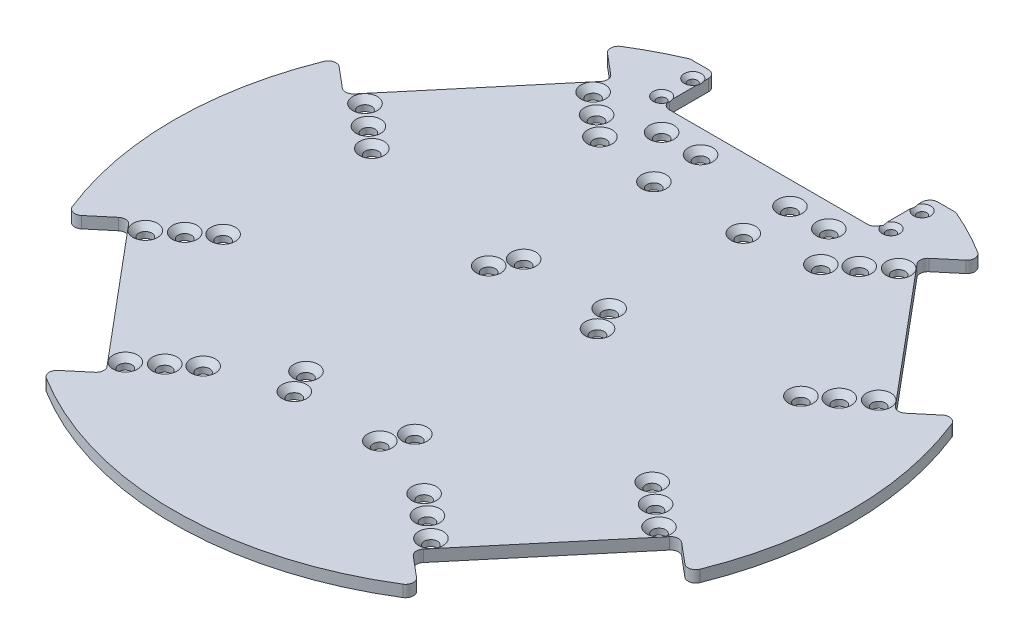
SolidWorks part; units mm, degrees
material "Liga 1060"
ref_plane "Plano frontal" through (0, 0, 0) normal (0, 0, 1) x (1, 0, 0)
ref_plane "Plano superior" through (0, 0, 0) normal (0, 1, 0) x (1, 0, 0)
ref_plane "Plano direito" through (0, 0, 0) normal (1, 0, 0) x (0, 0, -1)
sketch "Esboço1" plane through (0, 0, 0) normal (0, 1, 0) x (1, 0, 0)
  line L0 (0, 0) -> (0, 57.579) construction
  line L1 (0, 0) -> (28.8198, 0) construction
  circle A0 centre (0, 0) radius 87
  dimension "D1" = 174
extrude "Ressalto-extrusão2" add sketch "Esboço1" along normal blind 3
sketch "Esboço2" plane through (0, 3, 0) normal (0, 1, 0) x (1, 0, 0)
  line L0 (-87, 0) -> (87, 0) construction
  line L1 (0, 0) -> (66.6459, 55.9225) construction
  line L2 (0, 0) -> (66.6459, -55.9225) construction
  line L3 (48.2004, 72.4274) -> (79.697, 34.8912) construction
  line L4 (39.3908, 65.0353) -> (70.8874, 27.4991)
  line L9 (70.8874, 27.4991) -> (82.3942, 37.1544)
  line L10 (66.6459, 55.9225) -> (82.3942, 37.1544)
  line L11 (66.6459, 55.9225) -> (50.8976, 74.6906)
  line L12 (39.3908, 65.0353) -> (50.8976, 74.6906)
  line L13 (50.8976, -74.6906) -> (82.3942, -37.1544)
  line L14 (50.8976, -74.6906) -> (39.3908, -65.0353)
  line L15 (39.3908, -65.0353) -> (70.8874, -27.4991)
  line L16 (70.8874, -27.4991) -> (82.3942, -37.1544)
  line L17 (0, -87) -> (0, 87) construction
  line L18 (-39.3908, -65.0353) -> (-70.8874, -27.4991)
  line L19 (-50.8976, -74.6906) -> (-82.3942, -37.1544)
  line L20 (-50.8976, -74.6906) -> (-39.3908, -65.0353)
  line L21 (-70.8874, -27.4991) -> (-82.3942, -37.1544)
  line L22 (-66.6459, 55.9225) -> (-82.3942, 37.1544)
  line L23 (-70.8874, 27.4991) -> (-82.3942, 37.1544)
  line L24 (-48.2004, 72.4274) -> (-79.697, 34.8912) construction
  line L25 (-39.3908, 65.0353) -> (-50.8976, 74.6906)
  line L26 (-66.6459, 55.9225) -> (-50.8976, 74.6906)
  line L27 (-39.3908, 65.0353) -> (-70.8874, 27.4991)
  line L28 (48.2004, -72.4274) -> (79.697, -34.8912) construction
  circle A0 centre (0, 0) radius 87 construction
  point P11 (63.9487, 53.6593)
  point P12 (55.1391, 46.2672)
  point P20 (66.6459, -55.9225)
  point P28 (-66.6459, -55.9225)
  dimension "D1" = 40
  dimension "D2" = 40
  dimension "D3" = 49
  dimension "D4" = 11.5
  dimension "D5" = 49
  dimension "D6" = 49
  dimension "D7" = 11.5
extrude "Corte-extrusão2" cut sketch "Esboço2" against normal blind 3
fillet "Filete1" radius 2 16 edges at (-48.2004, 1.5, 72.4274) (-39.3908, 1.5, 65.0353) (-70.8874, 1.5, 27.4991) (-79.697, 1.5, 34.8912) (-79.697, 1.5, -34.8912) (-70.8874, 1.5, -27.4991) (-39.3908, 1.5, -65.0353) (-48.2004, 1.5, -72.4274) (48.2004, 1.5, -72.4274) (39.3908, 1.5, -65.0353) (70.8874, 1.5, -27.4991) (79.697, 1.5, -34.8912) (79.697, 1.5, 34.8912) (70.8874, 1.5, 27.4991) (39.3908, 1.5, 65.0353) (48.2004, 1.5, 72.4274)
sketch "Esboço3" plane through (0, 3, 0) normal (0, 1, 0) x (1, 0, 0)
  line L0 (0, 0) -> (-55.1391, 46.2672) construction
  line L1 (-69.6019, 29.0312) -> (-40.6764, 63.5032) construction
  line L2 (0, 0) -> (-55.1391, -46.2672) construction
  line L4 (-40.6764, -63.5032) -> (-69.6019, -29.0312) construction
  line L6 (0, 87) -> (0, -87) construction
  line L7 (-68.5252, -30.3144) -> (-41.7531, -62.2201) construction
  line L8 (-41.7531, -62.2201) -> (-28.4239, -51.0356) construction
  line L9 (-68.5252, -30.3144) -> (-55.196, -19.1299) construction
  line L10 (-68.5252, 30.3144) -> (-41.7531, 62.2201) construction
  line L11 (-69.6019, 29.0312) -> (-40.6764, 63.5032) construction
  line L12 (-41.7531, 62.2201) -> (-28.4239, 51.0356) construction
  line L13 (-68.5252, 30.3144) -> (-55.196, 19.1299) construction
  line L14 (0, 0) -> (55.1391, -46.2672) construction
  line L15 (68.5252, -30.3144) -> (55.196, -19.1299) construction
  line L16 (41.7531, -62.2201) -> (28.4239, -51.0356) construction
  line L17 (68.5252, -30.3144) -> (41.7531, -62.2201) construction
  line L18 (68.5252, 30.3144) -> (55.196, 19.1299) construction
  line L19 (41.7531, 62.2201) -> (28.4239, 51.0356) construction
  line L20 (68.5252, 30.3144) -> (41.7531, 62.2201) construction
  line L21 (0, 0) -> (55.1391, 46.2672) construction
  arc A0 (45.8895, 73.9131) -> (-45.8895, 73.9131) centre (0, 0) ccw construction
  arc A1 (-45.8895, -73.9131) -> (45.8895, -73.9131) centre (0, 0) ccw construction
  point P16 (-39.3017, -60.1632)
  point P19 (-55.1391, -46.2672)
  point P21 (-33.7862, -55.5351)
  point P22 (-66.0739, -28.2574)
  point P23 (-60.5583, -23.6294)
  point P27 (-66.0739, 28.2574)
  point P28 (-60.5583, 23.6294)
  point P31 (-39.3017, 60.1632)
  point P32 (-33.7862, 55.5351)
  point P39 (-55.1391, 46.2672)
  point P43 (60.5583, -23.6294)
  point P44 (66.0739, -28.2574)
  point P45 (33.7862, -55.5351)
  point P46 (55.1391, -46.2672)
  point P47 (39.3017, -60.1632)
  point P53 (55.1391, 46.2672)
  point P54 (33.7862, 55.5351)
  point P55 (39.3017, 60.1632)
  point P56 (60.5583, 23.6294)
  point P57 (66.0739, 28.2574)
  dimension "D1" = 41.65
  dimension "D2" = 3.2
  dimension "D3" = 7.2
  dimension "D4" = 7
  dimension "D5" = 3.2
  dimension "D6" = 7.2
  dimension "D7" = 7
  dimension "D8" = 41.65
  dimension "D9" = 3.2
  dimension "D10" = 7.2
  dimension "D11" = 7
  dimension "D12" = 3.2
  dimension "D13" = 7.2
  dimension "D14" = 7
hole_wizard "Escareado para parafuso com cabeça escareada chata de M32" positions "3DSketch2" profile "Esboço4" countersink size "M3" standard "ISO" end condition through all
sketch3d "3DSketch2"
  point P0 (-66.0739, 3, 28.2574)
  point P3 (-60.5583, 3, 23.6294)
  point P6 (-55.196, 3, 19.1299)
  point P9 (-39.3017, 3, 60.1632)
  point P12 (-33.7862, 3, 55.5351)
  point P15 (-28.4239, 3, 51.0356)
  point P18 (-66.0739, 3, -28.2574)
  point P21 (-60.5583, 3, -23.6294)
  point P24 (-55.196, 3, -19.1299)
  point P27 (-39.3017, 3, -60.1632)
  point P30 (-33.7862, 3, -55.5351)
  point P33 (-28.4239, 3, -51.0356)
  point P36 (39.3017, 3, -60.1632)
  point P39 (33.7862, 3, -55.5351)
  point P42 (28.4239, 3, -51.0356)
  point P45 (66.0739, 3, -28.2574)
  point P48 (60.5583, 3, -23.6294)
  point P51 (55.196, 3, -19.1299)
  point P54 (66.0739, 3, 28.2574)
  point P57 (60.5583, 3, 23.6294)
  point P60 (55.196, 3, 19.1299)
  point P63 (28.4239, 3, 51.0356)
  point P66 (33.7862, 3, 55.5351)
  point P69 (39.3017, 3, 60.1632)
sketch "Esboço4" plane through (-66.0739, 3, 28.2574) normal (1, 0, 0) x (0, 0, 1)
  line L0 (0, 0) -> (0, 3)
  line L1 (0, 3) -> (1.7, 3)
  line L2 (1.7, 3) -> (1.7, 1.45)
  line L3 (1.7, 1.45) -> (3.15, 0)
  line L5 (3.15, 0) -> (0, 0)
  line L6 (-1.7, 1.45) -> (-3.15, 0) construction
  line L11 (0, -6.35) -> (0, 107.95) construction
  dimension "Thru Hole Dia." = 3.4
  dimension "Thru Hole Depth" = 3
  dimension "Near C'Sink Dia." = 6.3
  dimension "Near C'Sink Angle" = 90
sketch "Esboço5" plane through (0, 3, 0) normal (0, 1, 0) x (1, 0, 0)
  line L0 (0, 0) -> (0, 80) construction
  line L1 (0, 80) -> (0, 87) construction
  line L2 (-34.1906, 80) -> (34.1906, 80)
  line L3 (-34.1906, 87) -> (34.1906, 87)
  line L4 (-34.1906, 87) -> (-34.1906, 80)
  line L5 (34.1906, 87) -> (34.1906, 80)
  line L6 (0, 66) -> (27.5, 66)
  line L7 (27.5, 66) -> (27.5, 80)
  line L8 (27.5, 80) -> (-27.5, 80)
  line L9 (-27.5, 80) -> (-27.5, 66)
  line L10 (-27.5, 66) -> (0, 66)
  arc A0 (45.8895, 73.9131) -> (-45.8895, 73.9131) centre (0, 0) ccw construction
  point P10 (0, 80)
  point P13 (0, 87)
  dimension "D1" = 80
  dimension "D2" = 55
  dimension "D3" = 14
extrude "Corte-extrusão3" cut sketch "Esboço5" against normal blind 3 contours L9 L10 L6 L7 L2 | L5 L3 L4 L2
fillet "Filete2" radius 2 6 edges at (-34.1906, 1.5, -80) (27.5, 1.5, -80) (27.5, 1.5, -66) (34.1906, 1.5, -80) (-27.5, 1.5, -66) (-27.5, 1.5, -80)
sketch "Esboço6" plane through (0, 0, 0) normal (0, -1, 0) x (1, 0, 0)
  line L0 (0, 0) -> (0, 87) construction
  line L1 (-12.5, 44) -> (12.5, 44) construction
  point P3 (0, 44)
  point P7 (0, 44)
  dimension "D1" = 87
  dimension "D2" = 43
  dimension "D3" = 25
sketch "Esboço7" plane through (0, 3, 0) normal (0, 1, 0) x (1, 0, 0)
  line L0 (-27.5, 80) -> (-27.5, 66) construction
  line L1 (-33.7787, 80) -> (-29.5, 80) construction
  line L2 (-27.5, 78) -> (-27.5, 68) construction
  line L3 (-25.5, 66) -> (25.5, 66) construction
  line L4 (-27.5, 66) -> (-27.5, 62) construction
  line L5 (-27.5, 62) -> (-19.5, 62) construction
  line L6 (-19.5, 62) -> (-11.5, 62) construction
  line L7 (-19.5, 62) -> (-19.5, 56) construction
  line L8 (-19.5, 56) -> (-11.5, 56) construction
  line L9 (-11.5, 56) -> (-11.5, 62) construction
  line L10 (0, 66) -> (0, 0) construction
  line L11 (11.5, 56) -> (11.5, 62) construction
  line L12 (19.5, 56) -> (11.5, 56) construction
  line L13 (19.5, 62) -> (19.5, 56) construction
  line L14 (19.5, 62) -> (11.5, 62) construction
  dimension "D1" = 4
  dimension "D2" = 8
  dimension "D3" = 8
  dimension "D4" = 6
sketch "Esboço8" plane through (0, 3, 0) normal (0, 1, 0) x (1, 0, 0)
  line L0 (0, 66) -> (0, 60) construction
  line L1 (-25.5, 66) -> (25.5, 66) construction
  line L2 (-27.5, 68) -> (-27.5, 60) construction
  line L3 (27.5, 68) -> (27.5, 60) construction
  line L4 (27.5, 60) -> (0, 60) construction
  line L5 (0, 60) -> (-27.5, 60) construction
  line L6 (-11.5, 60) -> (-11.5, 48) construction
  line L7 (11.5, 60) -> (11.5, 48) construction
  arc A0 (-27.5, 68) -> (-25.5, 66) centre (-25.5, 68) ccw construction
  point P13 (-16.5, 60)
  point P14 (21.5, 60)
  point P16 (16.5, 60)
  point P17 (-21.5, 60)
  point P18 (-11.5, 60)
  point P19 (11.5, 60)
  point P24 (-11.5, 54)
  point P25 (11.5, 54)
  dimension "D1" = 6
  dimension "D2" = 6
  dimension "D3" = 5
  dimension "D4" = 5
  dimension "D5" = 6
  dimension "D6" = 5
  dimension "D7" = 5
  dimension "D8" = 6
  dimension "D9" = 6
  dimension "D10" = 6
  dimension "D11" = 6
hole_wizard "Escareado para parafuso com cabeça escareada chata de M33" positions "3DSketch5" profile "Esboço11" countersink size "M3" standard "ISO"
sketch3d "3DSketch5"
  point P0 (-21.5, 3, -60)
  point P3 (-11.5, 3, -60)
  point P6 (-11.5, 3, -48)
  point P9 (11.5, 3, -48)
  point P12 (11.5, 3, -60)
  point P15 (21.5, 3, -60)
sketch "Esboço11" plane through (-21.5, 3, -60) normal (1, 0, 0) x (0, 0, 1)
  line L0 (0, 0) -> (0, 8.2715)
  line L1 (0, 8.2715) -> (1.7, 7.25)
  line L2 (1.7, 7.25) -> (1.7, 1.45)
  line L3 (1.7, 1.45) -> (3.15, 0)
  line L5 (3.15, 0) -> (0, 0)
  line L6 (-1.7, 1.45) -> (-3.15, 0) construction
  line L10 (0, 8.2715) -> (-1.7, 7.25) construction
  line L11 (0, -6.35) -> (0, 107.95) construction
  dimension "Hole Dia." = 3.4
  dimension "Hole Depth" = 7.25
  dimension "Near C'Sink Dia." = 6.3
  dimension "Near C'Sink Angle" = 90
  dimension "Drill Angle" = 118
sketch "Esboço12" plane through (0, 3, 0) normal (0, 1, 0) x (1, 0, 0)
  line L0 (0, 0) -> (0, -87) construction
  line L1 (0, 0) -> (0, 66) construction
  line L2 (-25.5, 66) -> (25.5, 66) construction
  line L3 (-11, 14) -> (11, 14) construction
  line L4 (-11, -45) -> (11, -45) construction
  line L5 (-14, -39) -> (14, -39)
  line L6 (-14, 8) -> (14, 8)
  arc A0 (-45.8895, -73.9131) -> (45.8895, -73.9131) centre (0, 0) ccw construction
  point P6 (0, -45)
  point P7 (0, 14)
  point P14 (0, 14)
  point P17 (0, -45)
  point P21 (0, -39)
  point P23 (0, 8)
  dimension "D1" = 42
  dimension "D2" = 59
  dimension "D3" = 22
  dimension "D4" = 22
  dimension "D5" = 28
  dimension "D6" = 6
  dimension "D7" = 28
  dimension "D8" = 6
hole_wizard "Escareado para parafuso com cabeça escareada chata de M31" positions "3DSketch6" profile "Esboço13" countersink size "M3" standard "ISO"
sketch3d "3DSketch6"
  point P0 (11, 3, -14)
  point P3 (-11, 3, -14)
  point P6 (-11, 3, 45)
  point P9 (11, 3, 45)
  point P12 (-14, 3, 39)
  point P15 (14, 3, 39)
  point P19 (-14, 3, -8)
  point P22 (14, 3, -8)
sketch "Esboço13" plane through (11, 3, -14) normal (1, 0, 0) x (0, 0, 1)
  line L0 (0, 0) -> (0, 8.2715)
  line L1 (0, 8.2715) -> (1.7, 7.25)
  line L2 (1.7, 7.25) -> (1.7, 1.45)
  line L3 (1.7, 1.45) -> (3.15, 0)
  line L5 (3.15, 0) -> (0, 0)
  line L6 (-1.7, 1.45) -> (-3.15, 0) construction
  line L10 (0, 8.2715) -> (-1.7, 7.25) construction
  line L11 (0, -6.35) -> (0, 107.95) construction
  dimension "Hole Dia." = 3.4
  dimension "Hole Depth" = 7.25
  dimension "Near C'Sink Dia." = 6.3
  dimension "Near C'Sink Angle" = 90
  dimension "Drill Angle" = 118
sketch "Esboço14" plane through (0, 3, 0) normal (0, 1, 0) x (1, 0, 0)
  line L0 (-27.5, 78) -> (-27.5, 68) construction
  line L1 (29.5, 80) -> (29.5, 65) construction
  line L2 (-29.5, 80) -> (-29.5, 65) construction
  line L3 (-33.7787, 80) -> (-29.5, 80) construction
  line L4 (29.5, 80) -> (33.7787, 80) construction
  line L5 (27.5, 68) -> (27.5, 78) construction
  point P6 (-29.5, 72)
  point P7 (-29.5, 76)
  point P8 (-29.5, 68)
  point P15 (29.5, 76)
  point P16 (29.5, 72)
  point P17 (29.5, 68)
  dimension "D1" = 2
  dimension "D2" = 15
  dimension "D3" = 4
  dimension "D4" = 4
  dimension "D5" = 4
  dimension "D6" = 2
  dimension "D7" = 15
  dimension "D8" = 4
  dimension "D9" = 4
  dimension "D10" = 4
hole_wizard "Escareado para parafuso com cabeça escareada chata de M21" positions "3DSketch10" profile "Esboço17" countersink size "M2" standard "ISO"
sketch3d "3DSketch10"
  point P0 (-29.5, 3, -76)
  point P6 (-29.5, 3, -68)
  point P9 (29.5, 3, -76)
  point P15 (29.5, 3, -68)
sketch "Esboço17" plane through (-29.5, 3, -76) normal (1, 0, 0) x (0, 0, 1)
  line L0 (0, 0) -> (0, 10.721)
  line L1 (0, 10.721) -> (1.2, 10)
  line L2 (1.2, 10) -> (1.2, 1)
  line L3 (1.2, 1) -> (2.2, 0)
  line L5 (2.2, 0) -> (0, 0)
  line L6 (-1.2, 1) -> (-2.2, 0) construction
  line L10 (0, 10.721) -> (-1.2, 10) construction
  line L11 (0, -6.35) -> (0, 107.95) construction
  dimension "Hole Dia." = 2.4
  dimension "Hole Depth" = 10
  dimension "Near C'Sink Dia." = 4.4
  dimension "Near C'Sink Angle" = 90
  dimension "Drill Angle" = 118
